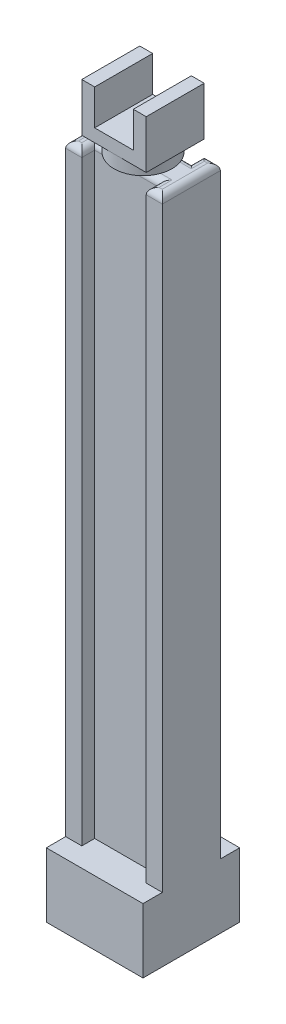
SolidWorks part; units mm, degrees
material "AISI 304"
ref_plane "Front Plane" through (0, 0, 0) normal (0, 0, 1) x (1, 0, 0)
ref_plane "Top Plane" through (0, 0, 0) normal (0, 1, 0) x (1, 0, 0)
ref_plane "Right Plane" through (0, 0, 0) normal (1, 0, 0) x (0, 0, -1)
sketch "Sketch2" plane through (0, 0, 0) normal (0, 1, 0) x (1, 0, 0)
  line L1 (-75, 75) -> (75, 75)
  line L2 (-75, 75) -> (-75, -75)
  line L3 (-75, -75) -> (75, -75)
  line L4 (75, 75) -> (75, -75)
  line L5 (-75, 75) -> (75, -75) construction
  line L6 (-75, -75) -> (75, 75) construction
  point P0 (0, 0)
  dimension "D1" = 150
  dimension "D2" = 150
extrude "Boss-Extrude1" add sketch "Sketch2" along normal blind 1035
sketch "Sketch3" plane through (0, 1035, 0) normal (0, 1, 0) x (-1, 0, 0)
  line L0 (-75, -75) -> (75, -75) construction
  line L1 (-50, -25) -> (50, -25)
  line L2 (-50, -25) -> (-50, -75)
  line L3 (-50, -75) -> (50, -75)
  line L4 (50, -25) -> (50, -75)
  line L5 (-50, -25) -> (50, -75) construction
  line L6 (-50, -75) -> (50, -25) construction
  line L7 (84.3437, 0) -> (-101.6201, 0) construction
  line L8 (-50, 75) -> (50, 25) construction
  line L9 (-50, 25) -> (50, 75) construction
  line L10 (50, 25) -> (50, 75)
  line L11 (-50, 75) -> (50, 75)
  line L12 (-50, 25) -> (-50, 75)
  line L13 (-50, 25) -> (50, 25)
  point P0 (0, -50)
  point P14 (0, 50)
  dimension "D1" = 100
  dimension "D2" = 50
extrude "Cut-Extrude3" cut sketch "Sketch3" against normal blind 935
sketch "Sketch4" plane through (0, 1035, 0) normal (0, 1, 0) x (-1, 0, 0)
  line L0 (75, -75) -> (75, 75) construction
  line L1 (75, -45) -> (-75, -45)
  line L2 (75, -45) -> (75, -75)
  line L3 (75, -75) -> (-75, -75)
  line L4 (-75, -45) -> (-75, -75)
  line L5 (75, -45) -> (-75, -75) construction
  line L6 (75, -75) -> (-75, -45) construction
  line L7 (75, 0) -> (-75, 0) construction
  line L8 (-75, 75) -> (-75, -75) construction
  line L9 (75, 75) -> (-75, 45) construction
  line L10 (75, 45) -> (-75, 75) construction
  line L11 (-75, 45) -> (-75, 75)
  line L12 (75, 75) -> (-75, 75)
  line L13 (75, 45) -> (75, 75)
  line L14 (75, 45) -> (-75, 45)
  point P0 (0, -60)
  point P16 (0, 60)
  dimension "D1" = 30
extrude "Cut-Extrude4" cut sketch "Sketch4" against normal up to surface (935 mm away) up to face at (0, 100, 50)
fillet "Fillet1" radius 10 12 edges at (50, 1035, 35) (0, 1035, 25) (-50, 1035, 35) (-62.5, 1035, 45) (-75, 1035, 0) (-62.5, 1035, -45) (-50, 1035, -35) (0, 1035, -25) (50, 1035, -35) (62.5, 1035, -45) (75, 1035, 0) (62.5, 1035, 45)
sketch "Sketch5" plane through (0, 1035, 0) normal (0, 1, 0) x (-1, 0, 0)
  circle A0 centre (0, 0) radius 45
  dimension "D1" = 90
extrude "Boss-Extrude2" add sketch "Sketch5" along normal blind 20
sketch "Sketch6" plane through (0, 0, 0) normal (0, 0, 1) x (1, 0, 0)
  line L0 (45, 1055) -> (-45, 1055) construction
  line L1 (-50, 1130) -> (50, 1130)
  line L2 (-50, 1130) -> (-50, 1055)
  line L3 (-50, 1055) -> (50, 1055)
  line L4 (50, 1130) -> (50, 1055)
  line L5 (-50, 1130) -> (50, 1055) construction
  line L6 (-50, 1055) -> (50, 1130) construction
  point P0 (0, 1092.5)
  dimension "D1" = 75
  dimension "D2" = 100
extrude "Boss-Extrude3" add sketch "Sketch6" along normal blind 90 from offset 45 offset against normal yes
sketch "Sketch7" plane through (0, 0, 45) normal (0, 0, 1) x (1, 0, 0)
  line L0 (50, 1130) -> (-50, 1130) construction
  line L1 (-30, 1185) -> (30, 1185)
  line L2 (-30, 1185) -> (-30, 1075)
  line L3 (-30, 1075) -> (30, 1075)
  line L4 (30, 1185) -> (30, 1075)
  line L5 (-30, 1185) -> (30, 1075) construction
  line L6 (-30, 1075) -> (30, 1185) construction
  line L7 (-50, 1055) -> (0, 1055) construction
  point P0 (0, 1130)
  dimension "D1" = 60
  dimension "D2" = 20
extrude "Cut-Extrude5" cut sketch "Sketch7" against normal up to surface (90 mm away) up to face at (0, 1085, -45)
